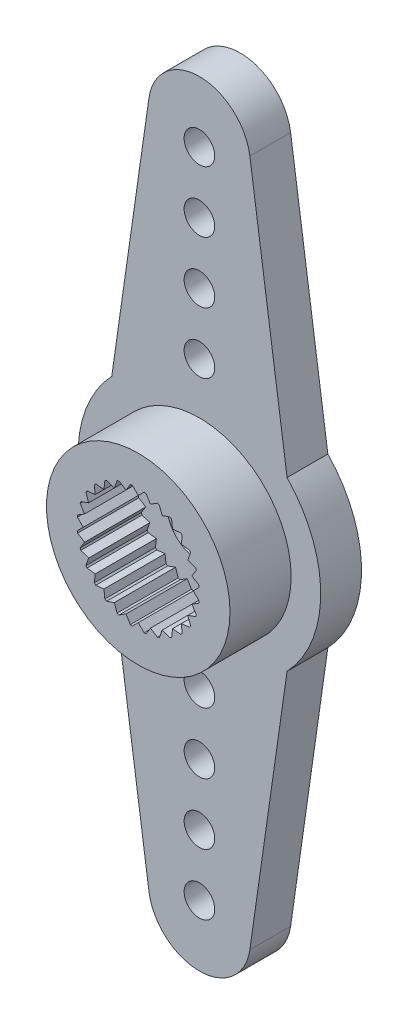
SolidWorks part; units mm, degrees
ref_plane "Plan de face" through (0, 0, 0) normal (0, 0, 1) x (1, 0, 0)
ref_plane "Plan de dessus" through (0, 0, 0) normal (0, 1, 0) x (1, 0, 0)
ref_plane "Plan de droite" through (0, 0, 0) normal (1, 0, 0) x (0, 0, -1)
sketch "Esquisse1" plane through (0, 0, 0) normal (0, 0, 1) x (1, 0, 0)
  circle A0 centre (0, 0) radius 5.95
  circle A1 centre (0, 0) radius 1.6
  dimension "D1" = 11.9
  dimension "D2" = 3.2
extrude "Boss.-Extru.1" add sketch "Esquisse1" along normal blind 5
sketch "Esquisse2" plane through (0, 0, 5) normal (0, 0, 1) x (1, 0, 0)
  circle A0 centre (0, 0) radius 3
  dimension "D1" = 6
extrude "Enlèv. mat.-Extru.1" cut sketch "Esquisse2" against normal blind 3
sketch "Esquisse3" plane through (0, 0, 5) normal (0, 0, 1) x (1, 0, 0)
  circle A0 centre (0, 0) radius 5.95
  circle A1 centre (0, 0) radius 4.5
  circle A2 centre (0, 0) radius 3 construction
  circle A3 centre (0, 0) radius 5.95 construction
  dimension "D1" = 1.5
extrude "Enlèv. mat.-Extru.2" cut sketch "Esquisse3" against normal blind 3
sketch "Esquisse4" plane through (0, 0, 0) normal (0, 0, -1) x (-1, 0, 0)
  line L0 (-4.3, 4.1125) -> (-2.4747, 16.8545)
  line L1 (2.4747, 16.8545) -> (4.3, 4.1125)
  line L2 (-5.2729, 19) -> (6.8365, 19) construction
  line L3 (0, 0) -> (0, 24.2526) construction
  circle A0 centre (0, 0) radius 5.95 construction
  arc A1 (-2.4747, 16.8545) -> (2.4747, 16.8545) centre (0, 16.5) cw
  arc A2 (-4.3, 4.1125) -> (4.3, 4.1125) centre (0, 0) cw
  dimension "D2" = 2.5
  dimension "D1" = 8.6
  dimension "D3" = 19
extrude "Boss.-Extru.2" add sketch "Esquisse4" against normal up to surface (2 mm away) up to face at (4.5, 0, 2)
pattern_circular "Répétition circulaire1" count 2 every 180 about axis through (0, 0, 0) along (0, 0, 1) of "Boss.-Extru.2"
sketch "Esquisse5" plane through (0, 0, 0) normal (0, 0, -1) x (-1, 0, 0)
  line L0 (0, 0) -> (0, 20.4605) construction
  circle A0 centre (0, 7) radius 0.75
  circle A1 centre (0, 10) radius 0.75
  circle A2 centre (0, 13) radius 0.75
  circle A3 centre (0, 16) radius 0.75
  dimension "D5" = 1.5
  dimension "D6" = 1.5
  dimension "D7" = 1.5
  dimension "D8" = 1.5
  dimension "D1" = 7
  dimension "D2" = 3
  dimension "D3" = 3
  dimension "D4" = 3
extrude "Enlèv. mat.-Extru.3" cut sketch "Esquisse5" against normal blind 3
pattern_circular "Répétition circulaire2" count 2 every 180 about axis through (0, 0, 0) along (0, 0, 1) of "Enlèv. mat.-Extru.3"
sketch "Esquisse6" plane through (0, 0, 5) normal (0, 0, 1) x (1, 0, 0)
  line L0 (-1.598, 3) -> (1.8482, 3) construction
  line L1 (0, 0) -> (0, 5.9454) construction
  line L2 (-0.3, 3) -> (0, 2.7)
  line L3 (0, 2.7) -> (0.3, 3)
  line L4 (0.3, 3) -> (-0.3, 3)
  circle A0 centre (0, 0) radius 3 construction
  dimension "D1" = 0.3
  dimension "D2" = 0.6
extrude "Boss.-Extru.3" add sketch "Esquisse6" against normal up to surface (3 mm away) up to face at (1.6, 0, 2)
pattern_circular "Répétition circulaire3" count 28 over 360 about axis through (0, 0, 0) along (0, 0, 1) of "Boss.-Extru.3"
sketch "Esquisse7" plane through (0, 0, 0) normal (0, 0, -1) x (-1, 0, 0)
  circle A0 centre (0, 0) radius 1.6
  circle A1 centre (0, 0) radius 3
  circle A2 centre (0, 0) radius 1.6 construction
  dimension "D1" = 6
extrude "Enlèv. mat.-Extru.4" cut sketch "Esquisse7" against normal blind 1
sketch "Esquisse8" plane through (0, 0, 0) normal (0, 0, -1) x (-1, 0, 0)
  circle A0 centre (0, 0) radius 3.4
  circle A1 centre (0, 0) radius 4.7
  circle A2 centre (0, 0) radius 3 construction
  dimension "D1" = 0.4
  dimension "D2" = 1.3
extrude "Enlèv. mat.-Extru.5" cut sketch "Esquisse8" against normal blind 1
